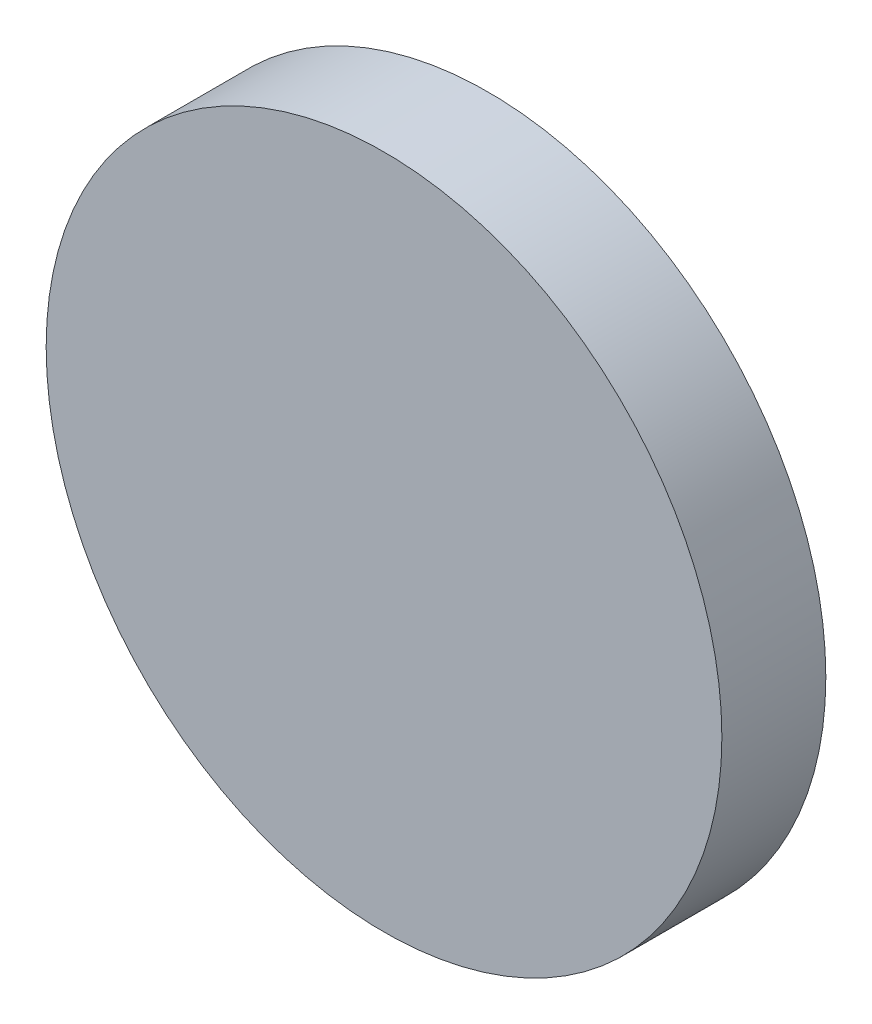
SolidWorks part; units mm, degrees
ref_plane "前视基准面" through (0, 0, 0) normal (0, 0, 1) x (1, 0, 0)
ref_plane "上视基准面" through (0, 0, 0) normal (0, 1, 0) x (1, 0, 0)
ref_plane "右视基准面" through (0, 0, 0) normal (1, 0, 0) x (0, 0, -1)
sketch "草图1" plane through (0, 0, 0) normal (0, 0, 1) x (1, 0, 0)
  circle A0 centre (0, 0) radius 3.25
  dimension "D1" = 6.5
extrude "凸台-拉伸1" add sketch "草图1" along normal blind 1
